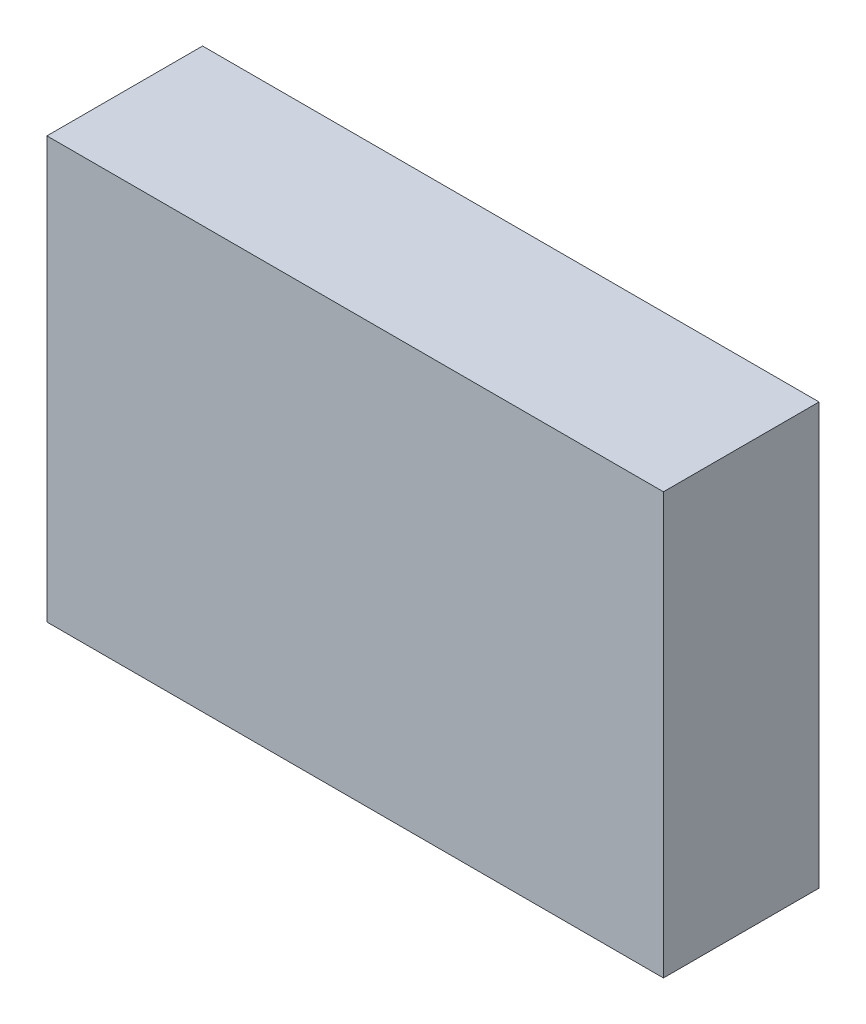
SolidWorks part; units mm, degrees
ref_plane "前视基准面" through (0, 0, 0) normal (0, 0, 1) x (1, 0, 0)
ref_plane "上视基准面" through (0, 0, 0) normal (0, 1, 0) x (1, 0, 0)
ref_plane "右视基准面" through (0, 0, 0) normal (1, 0, 0) x (0, 0, -1)
other "Configuration Table"
sketch "草图1" plane through (0, 0, 0) normal (0, 0, 1) x (1, 0, 0)
  line L1 (0, 0) -> (-206, 0)
  line L2 (0, 0) -> (0, 140.7)
  line L3 (0, 140.7) -> (-206, 140.7)
  line L4 (-206, 0) -> (-206, 140.7)
  dimension "D1" = 206
  dimension "D2" = 140.7
extrude "凸台-拉伸1" add sketch "草图1" along normal blind 52
